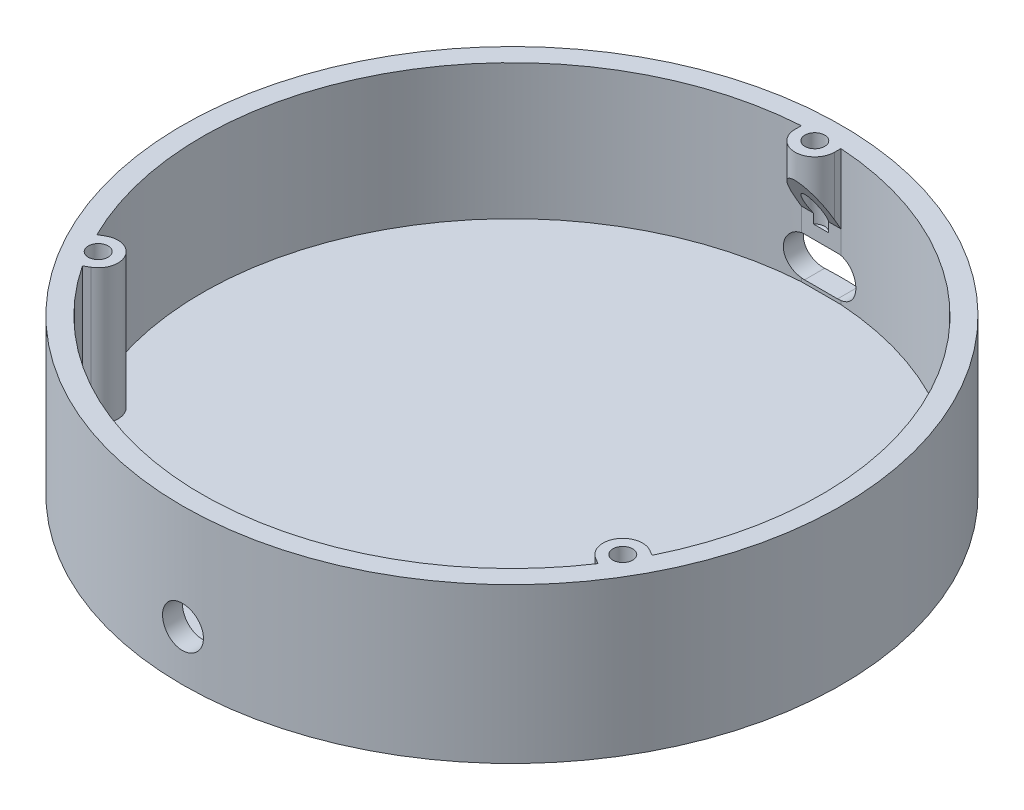
SolidWorks part; units mm, degrees
ref_plane "Front Plane" through (0, 0, 0) normal (0, 0, 1) x (1, 0, 0)
ref_plane "Top Plane" through (0, 0, 0) normal (0, 1, 0) x (1, 0, 0)
ref_plane "Right Plane" through (0, 0, 0) normal (1, 0, 0) x (0, 0, -1)
sketch "Sketch2" plane through (0, 0, 0) normal (0, 1, 0) x (1, 0, 0)
  line L0 (0, 0) -> (33.0185, 0) construction
  line L1 (0, 0) -> (0, 18.9008) construction
  circle A0 centre (0, 0) radius 50
  dimension "D1" = 100
extrude "Boss-Extrude1" add sketch "Sketch2" along normal blind 23.5
sketch "Sketch3" plane through (0, 23.5, 0) normal (0, 1, 0) x (1, 0, 0)
  line L0 (0, 0) -> (35.813, 0) construction
  line L1 (0, 0) -> (0, 30.2323)
  circle A0 centre (0, 0) radius 47
  dimension "D1" = 94
extrude "Cut-Extrude1" cut sketch "Sketch3" against normal blind 20.5
sketch "Sketch4" plane through (0, 3, 0) normal (0, 1, 0) x (1, 0, 0)
  line L0 (0, 45.95) -> (3, 45.95) construction
  line L1 (0, 0) -> (0, 52.9052) construction
  line L2 (-3, 48.95) -> (3, 48.95)
  line L3 (-3, 45.95) -> (-3, 48.95)
  line L4 (41.2939, -20.3769) -> (43.8919, -21.8769)
  line L5 (38.2939, -25.5731) -> (40.8919, -27.0731)
  line L6 (-3, 48.95) -> (3, 42.95) construction
  line L7 (-3, 42.95) -> (3, 48.95) construction
  line L8 (3, 45.95) -> (3, 48.95)
  line L9 (43.8919, -21.8769) -> (40.8919, -27.0731)
  line L10 (-38.2939, -25.5731) -> (-40.8919, -27.0731)
  line L11 (-41.2939, -20.3769) -> (-43.8919, -21.8769)
  line L12 (-40.8919, -27.0731) -> (-43.8919, -21.8769)
  line L13 (0, 0) -> (-75.8773, 0) construction
  arc A1 (0, 42.95) -> (3, 45.95) centre (0, 45.95) ccw
  arc A2 (0, 42.95) -> (-3, 45.95) centre (0, 45.95) cw
  arc A3 (37.1958, -21.475) -> (38.2939, -25.5731) centre (39.7939, -22.975) ccw
  arc A4 (37.1958, -21.475) -> (41.2939, -20.3769) centre (39.7939, -22.975) cw
  arc A6 (-37.1958, -21.475) -> (-41.2939, -20.3769) centre (-39.7939, -22.975) ccw
  arc A7 (-37.1958, -21.475) -> (-38.2939, -25.5731) centre (-39.7939, -22.975) cw
  point P16 (0, 48.95)
  point P36 (0, 0)
  dimension "D1" = 90
  dimension "D3" = 6
  dimension "D4" = 3
  dimension "D5" = 3
  dimension "D6" = 6
extrude "Boss-Extrude2" add sketch "Sketch4" along normal blind 20.5
sketch "Sketch7" plane through (0, 23.5, 0) normal (0, 1, 0) x (1, 0, 0)
  line L0 (0, 0) -> (0, 60.2819) construction
  circle A0 centre (0, 45.95) radius 1.5
  circle A1 centre (39.7939, -22.975) radius 1.5
  circle A2 centre (-39.7939, -22.975) radius 1.5
  point P14 (0, 0)
  dimension "D1" = 3
  dimension "D2" = 3
extrude "Cut-Extrude3" cut sketch "Sketch7" against normal blind 12
sketch "Sketch8" plane through (0, 0, 0) normal (0, 0, 1) x (1, 0, 0)
  line L0 (0, 0) -> (0, 55.1853) construction
  circle A0 centre (0, 7.6) radius 3.1
  dimension "D1" = 6.2
  dimension "D2" = 7.6
extrude "Cut-Extrude4" cut sketch "Sketch8" along normal through all
sketch "Sketch9" plane through (3, 0, 0) normal (1, 0, 0) x (0, 0, -1)
  line L0 (46.9042, 12.9416) -> (42.5816, 20.4285)
  line L1 (46.9042, 3) -> (46.9042, 23.5) construction
  line L2 (42.5816, 20.4285) -> (42.5816, 3)
  line L3 (46.9042, 12.9416) -> (46.9042, 3)
  line L4 (46.9042, 3) -> (42.5816, 3)
  line L5 (46.9042, 23.5) -> (46.9042, 3) construction
  dimension "D1" = 30
extrude "Cut-Extrude5" cut sketch "Sketch9" against normal up to surface (6 mm away) contours L4 L2 L0 L3
sketch "Sketch11" plane through (0, 0, 0) normal (0, 0, 1) x (1, 0, 0)
  line L0 (0, 0) -> (0, 24.2241) construction
  line L1 (-2.5, 6.5) -> (2.5, 6.5) construction
  line L2 (-2.5, 9.5) -> (2.5, 9.5)
  line L3 (-2.5, 3.5) -> (2.5, 3.5)
  line L4 (2.5, 9.5) -> (2.5, 3.5) construction
  line L5 (-5.5, 6.5) -> (5.5, 6.5) construction
  arc A0 (-2.5, 9.5) -> (-2.5, 3.5) centre (-2.5, 6.5) ccw
  arc A1 (2.5, 3.5) -> (2.5, 9.5) centre (2.5, 6.5) ccw
  point P4 (0, 6.5)
  point P12 (-5.5, 6.5)
  point P13 (5.5, 6.5)
  dimension "D1" = 6.5
  dimension "D2" = 3
  dimension "D3" = 11
extrude "Cut-Extrude6" cut sketch "Sketch11" against normal through all
